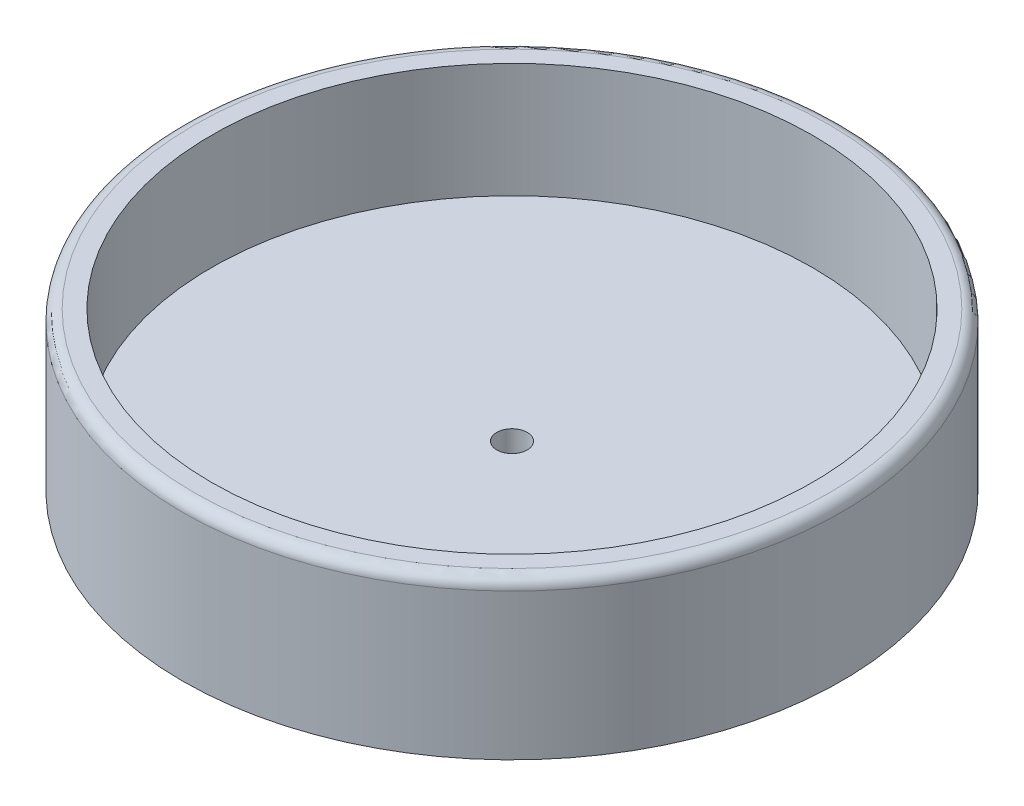
SolidWorks part; units mm, degrees
ref_plane "Front Plane" through (0, 0, 0) normal (0, 0, 1) x (1, 0, 0)
ref_plane "Top Plane" through (0, 0, 0) normal (0, 1, 0) x (1, 0, 0)
ref_plane "Right Plane" through (0, 0, 0) normal (1, 0, 0) x (0, 0, -1)
sketch "Sketch1" plane through (0, 0, 0) normal (0, 1, 0) x (1, 0, 0)
  circle A0 centre (0, 0) radius 73.025
  dimension "D1" = 146.05
extrude "Boss-Extrude1" add sketch "Sketch1" along normal blind 9.525
sketch "Sketch2" plane through (0, 9.525, 0) normal (0, 1, 0) x (1, 0, 0)
  circle A0 centre (0, 0) radius 73.025 construction
  circle A1 centre (0, 0) radius 73.025
  circle A2 centre (0, 0) radius 66.6115
  dimension "D1" = 133.223
extrude "Boss-Extrude2" add sketch "Sketch2" along normal blind 25.4
sketch "Sketch3" plane through (0, 0, 0) normal (0, -1, 0) x (1, 0, 0)
  point P0 (0, 0)
hole_wizard "CSK for 1/4 Flat Head Machine Screw (100)1" positions "Sketch5" profile "Sketch6" countersink size "1/4" standard "ANSI Inch"
sketch "Sketch5" plane through (0, 0, 0) normal (0, -1, 0) x (-1, 0, 0)
  point P0 (0, 0)
sketch "Sketch6" plane through (0, 0, 0) normal (1, 0, 0) x (0, 0, -1)
  line L0 (0, 0) -> (0, 12.1898)
  line L1 (0, 12.1898) -> (3.3782, 10.16)
  line L2 (3.3782, 10.16) -> (3.3782, 3.5593)
  line L3 (3.3782, 3.5593) -> (7.62, 0)
  line L5 (7.62, 0) -> (0, 0)
  line L6 (-3.3782, 3.5593) -> (-7.62, 0) construction
  line L10 (0, 12.1898) -> (-3.3782, 10.16) construction
  line L11 (0, -6.35) -> (0, 107.95) construction
  dimension "Hole Dia." = 6.7564
  dimension "Hole Depth" = 10.16
  dimension "Near C'Sink Dia." = 15.24
  dimension "Near C'Sink Angle" = 100
  dimension "Drill Angle" = 118
fillet "Fillet1" radius 2.54 1 edges at (0, 34.925, 73.025)
